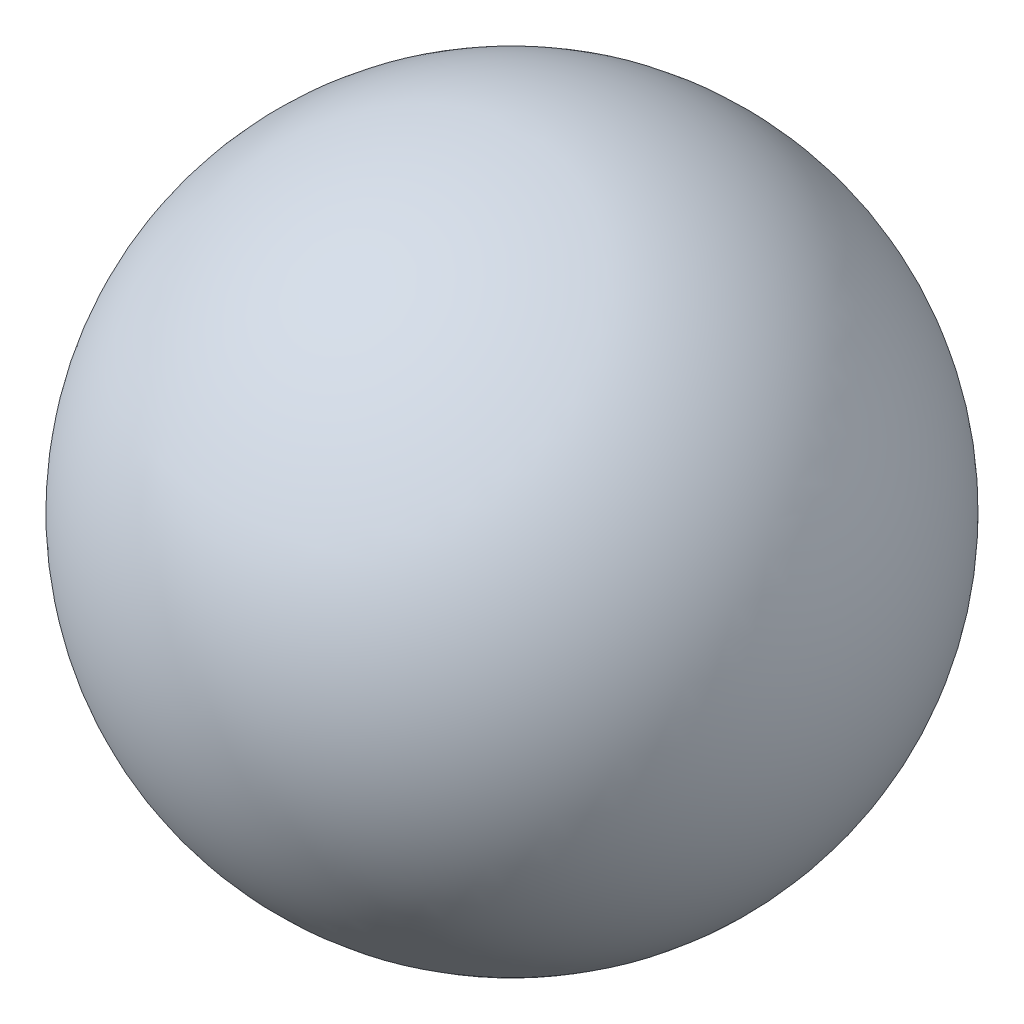
SolidWorks part; units mm, degrees
ref_plane "Plan de face" through (0, 0, 0) normal (0, 0, 1) x (1, 0, 0)
ref_plane "Plan de dessus" through (0, 0, 0) normal (0, 1, 0) x (1, 0, 0)
ref_plane "Plan de droite" through (0, 0, 0) normal (1, 0, 0) x (0, 0, -1)
sketch "Esquisse1" plane through (0, 0, 0) normal (0, 0, 1) x (1, 0, 0)
  line L0 (0, 0) -> (0, 4) construction
  line L1 (0, 4) -> (0, 5)
  line L2 (1.5, -3.7081) -> (1.5, -4.7697)
  arc A2 (0, 4) -> (1.5, -3.7081) centre (0, 0) cw
  arc A3 (0, 5) -> (1.5, -4.7697) centre (0, 0) cw
  dimension "D1" = 5
  dimension "D3" = 1
  dimension "D2" = 1.5
revolve "Révolution4" add sketch "Esquisse1" angle 360 about L0
